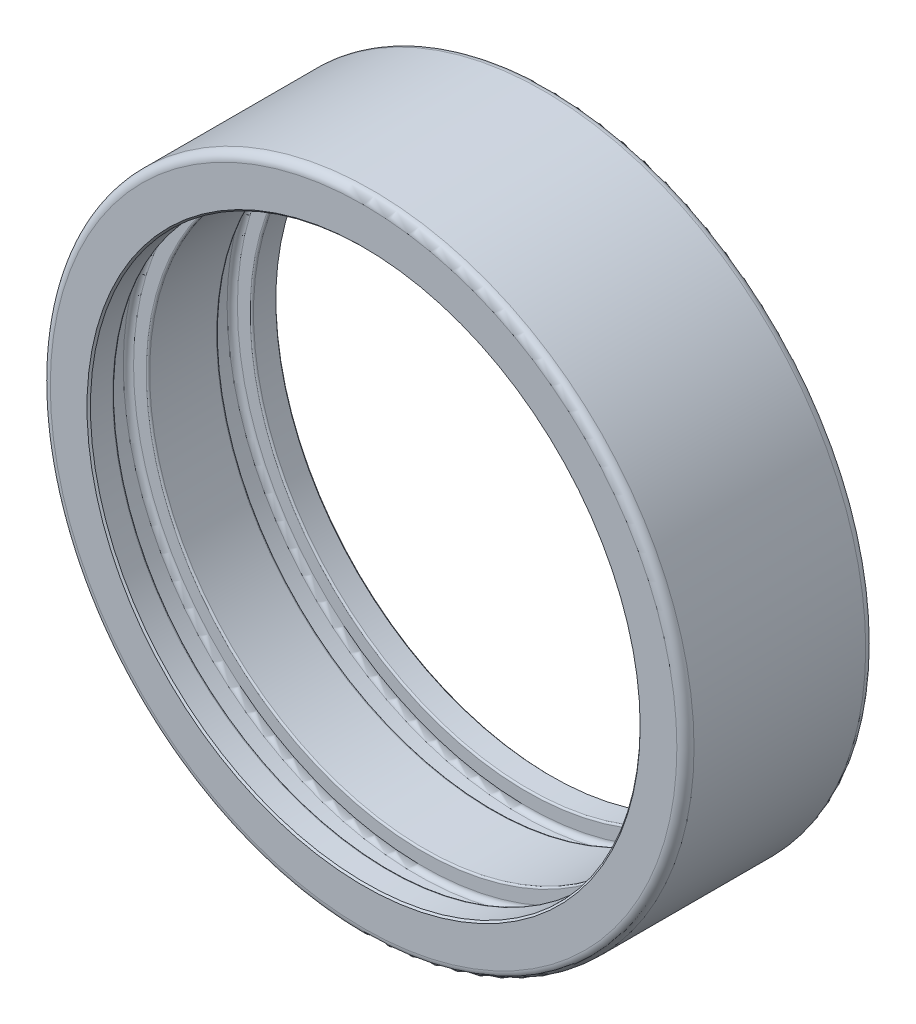
SolidWorks part; units mm, degrees
material "1.7131 (16MnCr5)"
ref_plane "Vorne" through (0, 0, 0) normal (0, 0, 1) x (1, 0, 0)
ref_plane "Oben" through (0, 0, 0) normal (0, 1, 0) x (1, 0, 0)
ref_plane "Rechts" through (0, 0, 0) normal (1, 0, 0) x (0, 0, -1)
sketch "Skizze1" plane through (0, 0, 0) normal (0, 0, 1) x (1, 0, 0)
  circle A0 centre (0, 0) radius 37.5
  circle A1 centre (0, 0) radius 32.025
  dimension "D1" = 75
  dimension "D2" = 64.05
extrude "Linear austragen1" add sketch "Skizze1" along normal blind 22
fillet "Verrundung1" radius 1 2 edges at (37.5, 0, 0) (37.5, 0, 22)
sketch "Skizze2" plane through (0, 0, 0) normal (1, 0, 0) x (0, 0, -1)
  line L0 (0, 0) -> (-36.3857, 0) construction
  line L1 (-11, 0) -> (-11, 41.4343) construction
  line L2 (-6.3, 34.3) -> (-3.6, 34.3)
  line L3 (-6.9, 33.7) -> (-6.9, 0)
  line L4 (-6.9, 0) -> (-3, 0)
  line L5 (-3, 33.7) -> (-3, 0)
  line L6 (-18.4, 34.3) -> (-15.7, 34.3)
  line L7 (-19, 33.7) -> (-19, 0)
  line L8 (-19, 0) -> (-15.1, 0)
  line L9 (-15.1, 33.7) -> (-15.1, 0)
  line L10 (0, -36.5) -> (0, 36.5) construction
  arc A0 (-6.9, 33.7) -> (-6.3, 34.3) centre (-6.3, 33.7) cw
  arc A1 (-3, 33.7) -> (-3.6, 34.3) centre (-3.6, 33.7) ccw
  arc A2 (-15.1, 33.7) -> (-15.7, 34.3) centre (-15.7, 33.7) ccw
  arc A3 (-19, 33.7) -> (-18.4, 34.3) centre (-18.4, 33.7) cw
  dimension "D5" = 0.6
  dimension "D1" = 3.9
  dimension "D2" = 3.9
  dimension "D3" = 11
  dimension "D4" = 68.6
  dimension "D6" = 3
revolve "Schnitt-Rotation1" cut sketch "Skizze2" angle 360 about L0
fillet "Verrundung2" radius 0.2 4 edges at (32.025, 0, 3) (32.025, 0, 6.9) (32.025, 0, 15.1) (32.025, 0, 19)
chamfer "Fase1" distance 0.2 angle 45 2 edges at (32.025, 0, 0) (32.025, 0, 22)
